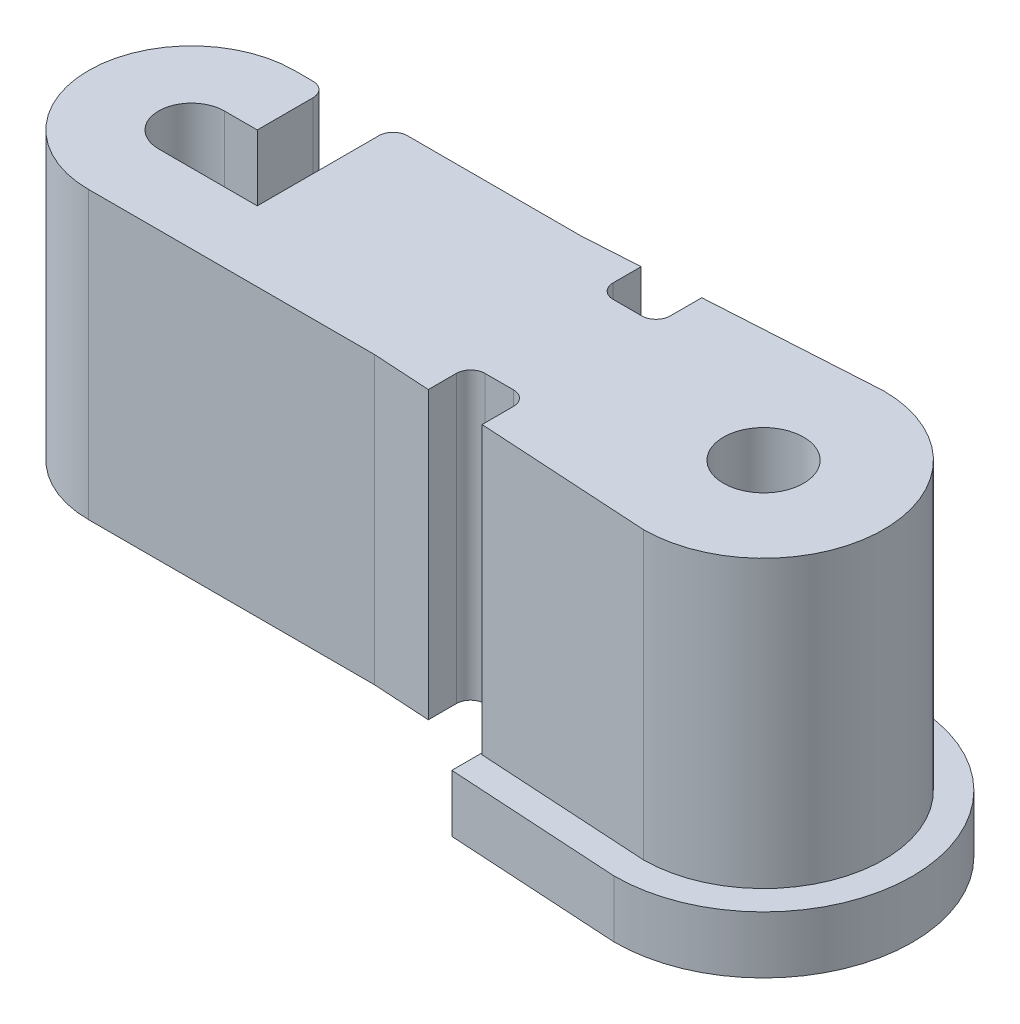
SolidWorks part; units mm, degrees
ref_plane "Front Plane" through (0, 0, 0) normal (0, 0, 1) x (1, 0, 0)
ref_plane "Top Plane" through (0, 0, 0) normal (0, 1, 0) x (1, 0, 0)
ref_plane "Right Plane" through (0, 0, 0) normal (1, 0, 0) x (0, 0, -1)
sketch "Sketch3" plane through (0, 0, 0) normal (0, 1, 0) x (1, 0, 0)
  line L0 (-5, 0.75) -> (0, 1.05) construction
  line L3 (0, -1.05) -> (-5, -0.75) construction
  line L4 (-2.5, 0.9) -> (-2, 0.93)
  line L6 (-4.25, 0) -> (-5.75, 0) construction
  line L7 (-2, 0.93) -> (-2, 0.56)
  line L8 (-2.5, 0.9) -> (-5, 0.9)
  line L9 (-2.5, 0.9) -> (-2.5, -0.9) construction
  line L10 (-2.5, -0.9) -> (-5, -0.9)
  line L11 (-5, 0.9) -> (-5, -0.9) construction
  line L12 (-2, 0.96) -> (-1.5, 0.96) construction
  line L13 (-2, 0.96) -> (-2, 0.56) construction
  line L14 (-2, 0.56) -> (-1.5, 0.56)
  line L15 (-1.5, 0.96) -> (-1.5, 0.56)
  line L16 (-1.5, -0.56) -> (-2, -0.56)
  line L17 (-1.5, -0.56) -> (-1.5, -0.96)
  line L18 (-1.5, -0.96) -> (-2, -0.96) construction
  line L19 (-2, -0.56) -> (-2, -0.96) construction
  line L21 (-2.5, -0.9) -> (-2, -0.93)
  line L22 (-2, -0.93) -> (-2, -0.56)
  line L23 (-1.5, 0.96) -> (0, 1.05)
  line L24 (0, -1.05) -> (-1.5, -0.96)
  circle A2 centre (0, 0) radius 0.6 construction
  circle A3 centre (0, 0) radius 0.4 construction
  circle A4 centre (-5, 0) radius 0.35 construction
  circle A5 centre (0, 0) radius 1.05 construction
  circle A6 centre (-5, 0) radius 0.75 construction
  arc A7 (-5, 0.9) -> (-5, -0.9) centre (-5, 0) ccw
  arc A8 (0, 1.05) -> (0, -1.05) centre (0, 0) cw
  point P4 (-2, -0.93)
  point P15 (-5, 0)
  point P16 (-2, 0.93)
  point P22 (-5, 0)
  dimension "D2" = 1.2
  dimension "D3" = 0.8
  dimension "D4" = 0.7
  dimension "D6" = 5
  dimension "D1" = 1.5
  dimension "D5" = 2.1
  dimension "D7" = 0.4
  dimension "D9" = 2.5
  dimension "D10" = 1.8
  dimension "D11" = 2.5
  dimension "D12" = 0.5
  dimension "D14" = 1.5
extrude "Boss-Extrude1" add sketch "Sketch3" along normal blind 2.5 contours L8 A7 L10 L21 L22 L16 L17 L24 A8 L23 L15 L14 L7 L4
sketch "Sketch4" plane through (0, 2.5, 0) normal (0, 1, 0) x (1, 0, 0)
  line L3 (-4.7125, 0.9) -> (-4.1375, 0.9)
  line L4 (-2.5, 0.9) -> (-5, 0.9) construction
  line L5 (-4.7125, 0.9) -> (-4.7125, 0.2875)
  line L6 (-4.1375, 0.9) -> (-4.1375, -0.2875)
  line L7 (-4.1375, -0.2875) -> (-5, -0.2875)
  line L8 (-5, 0.2875) -> (-4.7125, 0.2875)
  circle A0 centre (0, 0) radius 0.35
  circle A1 centre (-5, 0) radius 0.375 construction
  circle A2 centre (-5, 0) radius 0.2875 construction
  arc A3 (-5, 0.2875) -> (-4.9942, -0.2874) centre (-5, 0) ccw
  point P9 (0, 0)
  dimension "D1" = 0.7
  dimension "D2" = 0.75
  dimension "D4" = 0.575
  dimension "D3" = 0.575
extrude "Through Holes" cut sketch "Sketch4" against normal through all
fillet "Fillet1" radius 0.125 6 edges at (-2, 1.25, 0.56) (-1.5, 1.25, 0.56) (-1.5, 1.25, -0.56) (-2, 1.25, -0.56) (-4.7125, 1.25, -0.9) (-4.1375, 1.25, -0.9)
sketch "Sketch5" plane through (0, 0, 0) normal (0, 1, 0) x (1, 0, 0)
  line L2 (-1.515, -1.2096) -> (-1.515, 1.2096)
  line L4 (-1.515, 1.2096) -> (-0.0079, 1.3)
  line L5 (-0.0079, -1.3) -> (-1.515, -1.2096)
  line L6 (-1.515, 1.2096) -> (-0.0079, 1.3)
  line L7 (-0.0079, -1.3) -> (-1.515, -1.2096)
  circle A1 centre (0, 0) radius 0.125
  arc A2 (-0.0079, -1.3) -> (-0.0079, 1.3) centre (0, 0) ccw
  arc A3 (-0.0079, -1.3) -> (-0.0079, 1.3) centre (0, 0) ccw
  dimension "D2" = 0.25
  dimension "D1" = 0.25
extrude "Boss-Extrude2" add sketch "Sketch5" against normal blind 0.5
